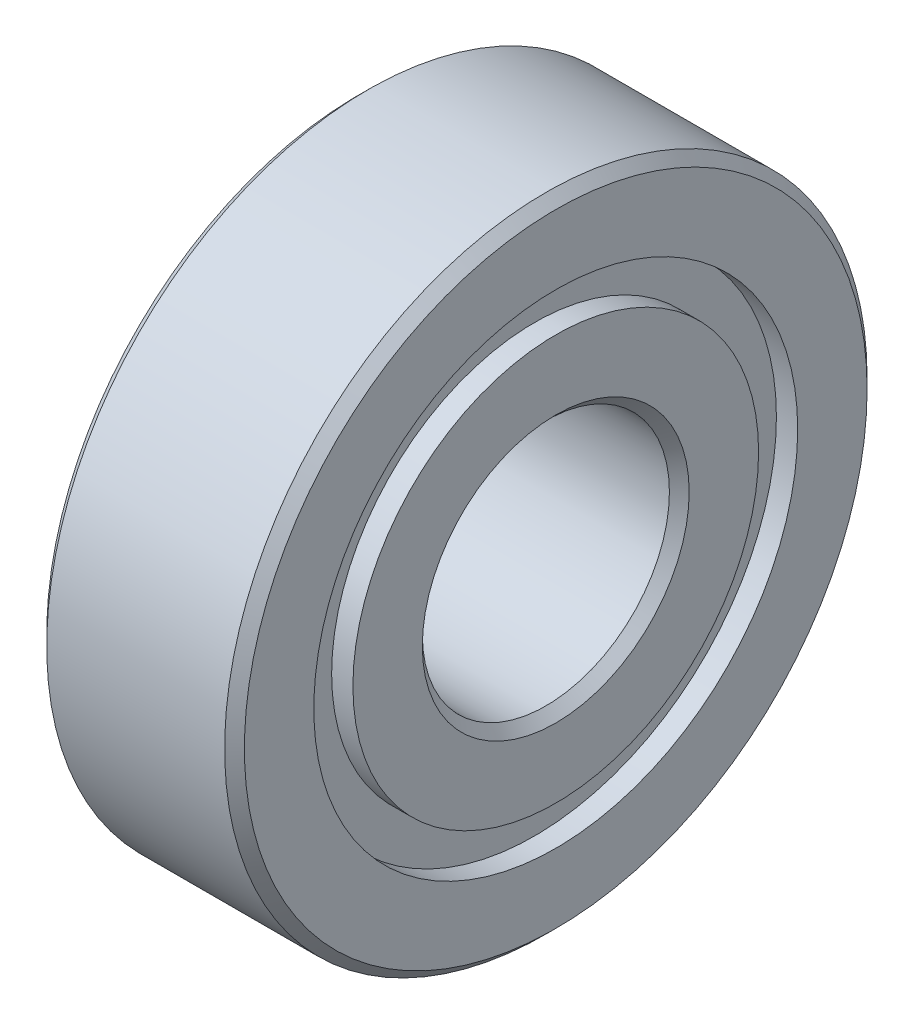
SolidWorks part; units mm, degrees
material "A8 (58-60 RC)"
ref_plane "Front" through (0, 0, 0) normal (0, 0, 1) x (1, 0, 0)
ref_plane "Top" through (0, 0, 0) normal (0, 1, 0) x (1, 0, 0)
ref_plane "Right" through (0, 0, 0) normal (1, 0, 0) x (0, 0, -1)
sketch "Sketch1" plane through (0, 0, 0) normal (0, 0, 1) x (1, 0, 0)
  line L0 (4, 12.6) -> (3.6, 13)
  line L1 (3.6, 13) -> (-3.6, 13)
  line L2 (-3.6, 13) -> (-4, 12.6)
  line L3 (-4, 12.6) -> (-4, 9.7912)
  line L4 (-4, 9.7912) -> (-3.1389, 9.7912)
  line L5 (-3.1389, 9.7912) -> (-3.1389, 8.2088)
  line L6 (-3.1389, 8.2088) -> (-4, 8.2088)
  line L7 (-4, 8.2088) -> (-4, 5.4)
  line L8 (-4, 5.4) -> (-3.6, 5)
  line L9 (-3.6, 5) -> (3.6, 5)
  line L10 (3.6, 5) -> (4, 5.4)
  line L11 (4, 5.4) -> (4, 8.2088)
  line L12 (4, 8.2088) -> (3.1389, 8.2088)
  line L13 (3.1389, 8.2088) -> (3.1389, 9.7912)
  line L14 (3.1389, 9.7912) -> (4, 9.7912)
  line L15 (4, 9.7912) -> (4, 12.6)
  line L16 (-4, 0) -> (4, 0) construction
revolve "Revolve1" add sketch "Sketch1" angle 360 about L16
